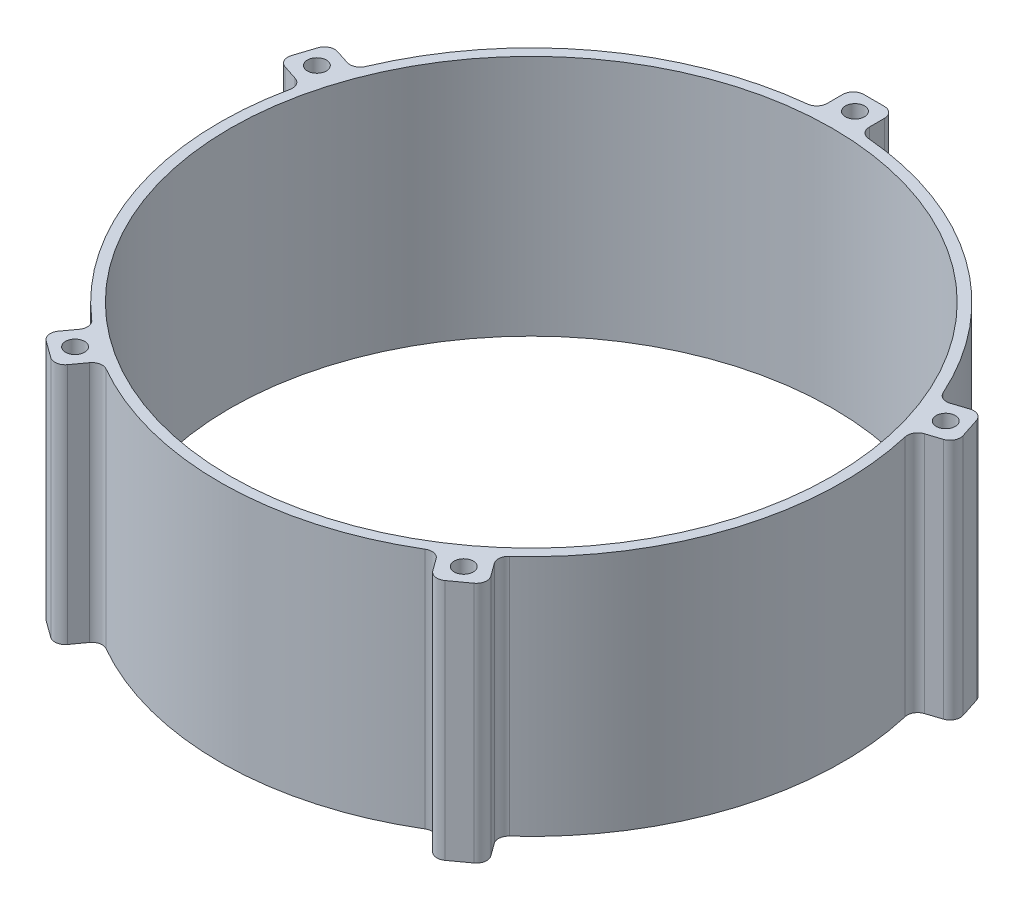
SolidWorks part; units mm, degrees
ref_plane "Front Plane" through (0, 0, 0) normal (0, 0, 1) x (1, 0, 0)
ref_plane "Top Plane" through (0, 0, 0) normal (0, 1, 0) x (1, 0, 0)
ref_plane "Right Plane" through (0, 0, 0) normal (1, 0, 0) x (0, 0, -1)
sketch "Sketch1" plane through (0, 0, 0) normal (0, 1, 0) x (1, 0, 0)
  circle A0 centre (46.8426, -26.1312) radius 90
  dimension "D1" = 180
extrude "Boss-Extrude1" add sketch "Sketch1" along normal blind 70
sketch "Sketch2" plane through (0, 70, 0) normal (0, 1, 0) x (1, 0, 0)
  circle A0 centre (46.8426, -26.1312) radius 87
  dimension "D1" = 174
sketch "Sketch3" plane through (0, 70, 0) normal (0, 1, 0) x (1, 0, 0)
  line L0 (139.7851, 11.4279) -> (128.3725, 7.7197)
  line L1 (39.8426, 73.8688) -> (51.8426, 73.8688)
  line L2 (39.8426, 73.8688) -> (39.8426, 61.8688)
  line L3 (39.8426, 61.8688) -> (51.8426, 61.8688)
  line L4 (51.8426, 73.8688) -> (51.8426, 61.8688)
  line L5 (139.7851, 11.4279) -> (143.4933, 0.0152)
  line L6 (143.4933, 0.0152) -> (132.0807, -3.693)
  line L7 (128.3725, 7.7197) -> (132.0807, -3.693)
  line L8 (111.2843, -102.9184) -> (104.2308, -93.2102)
  line L9 (111.2843, -102.9184) -> (101.576, -109.9718)
  line L10 (101.576, -109.9718) -> (94.5226, -100.2636)
  line L11 (104.2308, -93.2102) -> (94.5226, -100.2636)
  line L12 (-6.2728, -111.1474) -> (0.7806, -101.4392)
  line L13 (-6.2728, -111.1474) -> (-15.981, -104.094)
  line L14 (-15.981, -104.094) -> (-8.9276, -94.3858)
  line L15 (0.7806, -101.4392) -> (-8.9276, -94.3858)
  line L16 (-50.4262, -1.8869) -> (-39.0135, -5.5951)
  line L17 (-50.4262, -1.8869) -> (-46.718, 9.5258)
  line L18 (-46.718, 9.5258) -> (-35.3053, 5.8176)
  line L19 (-39.0135, -5.5951) -> (-35.3053, 5.8176)
  circle A0 centre (46.8426, -26.1312) radius 90 construction
  point P24 (46.8426, -26.1312)
  dimension "D1" = 12
  dimension "D2" = 12
  dimension "D3" = 5
  dimension "D4" = 88
  dimension "D5" = 5
extrude "Boss-Extrude2" add sketch "Sketch3" against normal up to surface (70 mm away) up to face at (46.8426, 0, 116.1312)
fillet "Fillet1" radius 3 20 edges at (-10.0214, 35, 95.8914) (-15.981, 35, 104.094) (-6.2728, 35, 111.1474) (-0.2347, 35, 102.8367) (95.6165, 35, 101.7692) (101.576, 35, 109.9718) (111.2843, 35, 102.9184) (105.2462, 35, 94.6077) (133.8506, 35, 3.1179) (143.4933, 35, -0.0152) (139.7851, 35, -11.4279) (130.0153, 35, -8.2535) (51.8426, 35, -63.7298) (51.8426, 35, -73.8688) (39.8426, 35, -73.8688) (39.8426, 35, -63.5962) (-37.0752, 35, -6.3927) (-40.6563, 35, 5.0613) (-46.718, 35, -9.5258) (-50.4262, 35, 1.8869)
extrude "Cut-Extrude3" cut sketch "Sketch2" against normal through all contours A0
sketch "Sketch5" plane through (0, 70, 0) normal (0, 1, 0) x (1, 0, 0)
  line L0 (97.2589, -104.0298) -> (99.8127, -107.5448) construction
  line L1 (104.0031, -108.2085) -> (108.8572, -104.6818) construction
  circle A0 centre (103.1973, -101.9955) radius 2.75
  circle A1 centre (-7.8941, -103.1711) radius 2.75
  circle A2 centre (-43.3412, 2.1198) radius 2.75
  circle A3 centre (45.8426, 68.3688) radius 2.75
  circle A4 centre (136.4084, 4.022) radius 2.75
  point P17 (46.8426, -26.1312)
  dimension "D1" = 5.5
  dimension "D2" = 6
  dimension "D3" = 5.5
  dimension "D4" = 5
extrude "Cut-Extrude4" cut sketch "Sketch5" against normal through all
